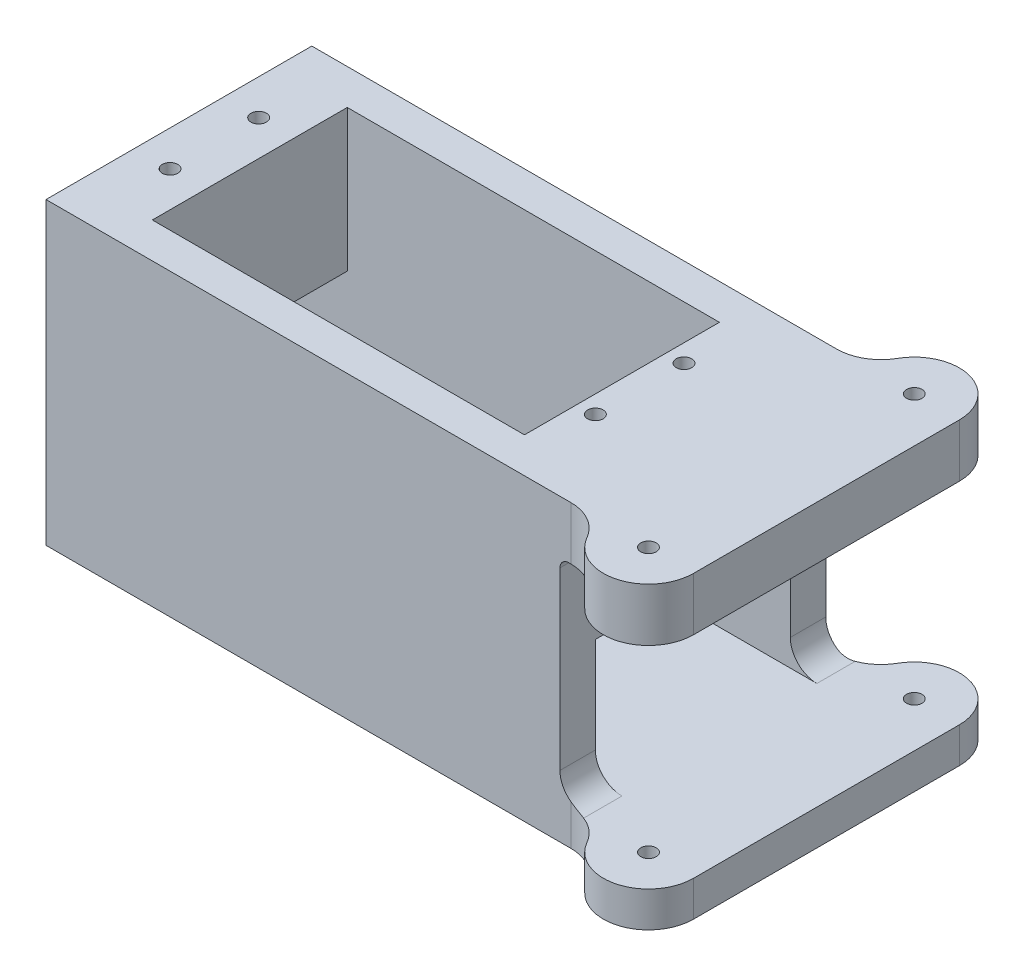
SolidWorks part; units mm, degrees
ref_plane "Front Plane" through (0, 0, 0) normal (0, 0, 1) x (1, 0, 0)
ref_plane "Top Plane" through (0, 0, 0) normal (0, 1, 0) x (1, 0, 0)
ref_plane "Right Plane" through (0, 0, 0) normal (1, 0, 0) x (0, 0, -1)
sketch "Sketch2" plane through (0, 0, 0) normal (0, 1, 0) x (1, 0, 0)
  line L0 (25, 15) -> (-25, 15)
  line L1 (21, 11) -> (-21, 11)
  line L2 (21, 11) -> (21, -11)
  line L3 (21, -11) -> (-21, -11)
  line L4 (-21, 11) -> (-21, -11)
  line L5 (21, 11) -> (-21, -11) construction
  line L6 (21, -11) -> (-21, 11) construction
  line L7 (-25, 15) -> (-25, -15)
  line L8 (25, -15) -> (-25, -15)
  line L9 (25, 15) -> (25, -15)
  point P0 (0, 0)
  dimension "D1" = 42
  dimension "D2" = 22
  dimension "D3" = 4
extrude "Boss-Extrude1" add sketch "Sketch2" along normal blind 28.8
sketch "Sketch3" plane through (0, 0, 0) normal (0, -1, 0) x (1, 0, 0)
  line L1 (25, 15) -> (-25, 15)
  line L2 (25, 15) -> (25, -15)
  line L3 (25, -15) -> (-25, -15)
  line L4 (-25, 15) -> (-25, -15)
  line L5 (25, 15) -> (-25, -15) construction
  line L6 (25, -15) -> (-25, 15) construction
  point P0 (0, 0)
extrude "Boss-Extrude2" add sketch "Sketch3" along normal blind 4
sketch "Sketch4" plane through (25, 0, 0) normal (1, 0, 0) x (0, 0, -1)
  line L0 (15, -4) -> (-15, -4) construction
  line L1 (-11, -4) -> (11, -4)
  line L2 (-11, -4) -> (-11, 13.8)
  line L3 (-11, 13.8) -> (11, 13.8)
  line L4 (11, -4) -> (11, 13.8)
  line L5 (-15, 28.8) -> (-15, -4) construction
  line L6 (15, 28.8) -> (15, -4) construction
  line L7 (-15, 28.8) -> (15, 28.8) construction
  dimension "D1" = 4
  dimension "D2" = 4
  dimension "D3" = 15
extrude "Cut-Extrude1" cut sketch "Sketch4" against normal blind 4
sketch "Sketch5" plane through (-25, 0, 0) normal (-1, 0, 0) x (0, 0, 1)
  line L4 (-15, 28.8) -> (-15, -4)
  line L5 (-15, -4) -> (15, -4)
  line L6 (15, -4) -> (15, 28.8)
  line L7 (15, 28.8) -> (-15, 28.8)
  line L8 (-15, 28.8) -> (-15, -4)
  line L9 (-15, -4) -> (15, -4)
  line L10 (15, -4) -> (15, 28.8)
  line L11 (15, 28.8) -> (-15, 28.8)
  dimension "D1" = 0
extrude "Boss-Extrude3" add sketch "Sketch5" along normal blind 4
sketch "Sketch6" plane through (25, 0, 0) normal (1, 0, 0) x (0, 0, -1)
  line L8 (-15, -4) -> (-11, -4)
  line L9 (-11, -4) -> (-11, 13.8)
  line L10 (-11, 13.8) -> (11, 13.8)
  line L11 (11, 13.8) -> (11, -4)
  line L12 (11, -4) -> (15, -4)
  line L13 (15, -4) -> (15, 28.8)
  line L14 (15, 28.8) -> (-15, 28.8)
  line L15 (-15, 28.8) -> (-15, -4)
  line L16 (-15, -4) -> (-11, -4)
  line L17 (-11, -4) -> (-11, 13.8)
  line L18 (-11, 13.8) -> (11, 13.8)
  line L19 (11, 13.8) -> (11, -4)
  line L20 (11, -4) -> (15, -4)
  line L21 (15, -4) -> (15, 28.8)
  line L22 (15, 28.8) -> (-15, 28.8)
  line L23 (-15, 28.8) -> (-15, -4)
  dimension "D1" = 0
extrude "Boss-Extrude4" add sketch "Sketch6" along normal blind 4
sketch "Sketch7" plane through (0, 28.8, 0) normal (0, 1, 0) x (1, 0, 0)
  circle A0 centre (23, -5) radius 0.875
  circle A1 centre (23, 5) radius 0.875
  circle A2 centre (-25, 5) radius 0.875
  circle A3 centre (-25, -5) radius 0.875
  dimension "D1" = 1.75
extrude "Cut-Extrude2" cut sketch "Sketch7" against normal blind 10
sketch "Sketch8" plane through (0, -4, 0) normal (0, -1, 0) x (1, 0, 0)
  line L0 (-29, -15) -> (29, -15) construction
  line L1 (38.9912, 15) -> (38.9912, -15) construction
  line L2 (20.903, -15) -> (30.2293, -15)
  line L3 (20.903, -15) -> (20.903, 15)
  line L4 (20.903, 15) -> (30.2293, 15)
  line L7 (44.0794, 15) -> (44.0794, -15)
  arc A2 (44.0794, 15) -> (34.5719, 17.5219) centre (38.9912, 15) ccw
  arc A3 (34.5719, -17.5219) -> (44.0794, -15) centre (38.9912, -15) ccw
  arc A4 (30.2293, 15) -> (34.5719, 17.5219) centre (30.2293, 20) ccw
  arc A5 (30.2293, -15) -> (34.5719, -17.5219) centre (30.2293, -20) cw
  circle A6 centre (38.9912, 15) radius 0.875
  circle A7 centre (38.9912, -15) radius 0.875
  point P8 (39.0381, 0)
  point P17 (33.903, 15)
  point P20 (33.903, -15)
  dimension "D3" = 5.0882
  dimension "D4" = 5.0882
  dimension "D6" = 5
  dimension "D7" = 1.75
  dimension "D1" = 13
  dimension "D2" = 30
  dimension "D5" = 30
extrude "Boss-Extrude5" add sketch "Sketch8" against normal up to surface (4 mm away) up to face at (0, 0, 0)
fillet "Fillet1" radius 3 2 edges at (29, 0, -13) (29, 0, 13)
ref_plane "Plane1" through (0, 12.4, 0) normal (0, 1, 0) x (1, 0, 0)
sketch "Sketch9" plane through (0, 28.8, 0) normal (0, 1, 0) x (1, 0, 0)
  line L0 (29, 15) -> (-29, 15) construction
  line L1 (30.2293, 15) -> (26.3329, 15)
  line L2 (26.3329, 15) -> (26.3329, -15)
  line L3 (-29, -15) -> (29, -15) construction
  line L4 (26.3329, -15) -> (30.2293, -15)
  line L6 (32, 15.3241) -> (32, 11)
  line L7 (32, 11) -> (-21, 11)
  line L8 (-21, 11) -> (-21, -11)
  line L9 (-21, -11) -> (32, -11)
  line L10 (32, -11) -> (32, -15.3241)
  line L11 (44.0794, -15) -> (44.0794, 15)
  line L17 (44.0794, -15) -> (44.0794, 15)
  arc A0 (32, 15.3241) -> (30.2293, 15) centre (30.2293, 20) cw
  arc A2 (30.2293, -15) -> (32, -15.3241) centre (30.2293, -20) cw
  circle A3 centre (38.9912, -15) radius 0.875
  arc A4 (32, 15.3241) -> (34.5719, 17.5219) centre (30.2293, 20) ccw
  arc A5 (34.5719, -17.5219) -> (32, -15.3241) centre (30.2293, -20) ccw
  arc A6 (34.5719, -17.5219) -> (44.0794, -15) centre (38.9912, -15) ccw
  arc A7 (44.0794, 15) -> (34.5719, 17.5219) centre (38.9912, 15) ccw
  arc A8 (32, 15.3241) -> (34.5719, 17.5219) centre (30.2293, 20) ccw
  arc A9 (34.5719, -17.5219) -> (32, -15.3241) centre (30.2293, -20) ccw
  arc A10 (34.5719, -17.5219) -> (44.0794, -15) centre (38.9912, -15) ccw
  arc A11 (44.0794, 15) -> (34.5719, 17.5219) centre (38.9912, 15) ccw
  circle A12 centre (38.9912, 15) radius 0.875
  dimension "D2" = 1.75
  dimension "D3" = 1.75
  dimension "D1" = 0
extrude "Boss-Extrude6" add sketch "Sketch9" against normal blind 5
fillet "Fillet2" radius 1 1 edges at (29, 23.8, 0)
sketch "Sketch11" plane through (0, 28.8, 0) normal (0, 1, 0) x (1, 0, 0)
  line L1 (21, 11) -> (-21, 11)
  line L2 (21, 11) -> (21, -11)
  line L3 (21, -11) -> (-21, -11)
  line L4 (-29, -15) -> (30.2293, -15)
  line L5 (44.0794, -15) -> (44.0794, 15)
  line L6 (30.2293, 15) -> (-29, 15)
  line L7 (-29, 15) -> (-29, -15)
  line L8 (-29, -15) -> (30.2293, -15)
  line L9 (44.0794, -15) -> (44.0794, 15)
  line L10 (30.2293, 15) -> (-29, 15)
  line L11 (-29, 15) -> (-29, -15)
  line L12 (-21, 11) -> (-21, -11)
  line L13 (21, 11) -> (-21, -11) construction
  line L14 (21, -11) -> (-21, 11) construction
  circle A0 centre (-25, 5) radius 0.875
  circle A1 centre (-25, -5) radius 0.875
  circle A2 centre (23, 5) radius 0.875
  circle A3 centre (23, -5) radius 0.875
  arc A4 (34.5719, -17.5219) -> (30.2293, -15) centre (30.2293, -20) ccw
  arc A5 (34.5719, -17.5219) -> (44.0794, -15) centre (38.9912, -15) ccw
  arc A6 (44.0794, 15) -> (34.5719, 17.5219) centre (38.9912, 15) ccw
  arc A7 (30.2293, 15) -> (34.5719, 17.5219) centre (30.2293, 20) ccw
  arc A8 (34.5719, -17.5219) -> (30.2293, -15) centre (30.2293, -20) ccw
  arc A9 (34.5719, -17.5219) -> (44.0794, -15) centre (38.9912, -15) ccw
  arc A10 (44.0794, 15) -> (34.5719, 17.5219) centre (38.9912, 15) ccw
  arc A11 (30.2293, 15) -> (34.5719, 17.5219) centre (30.2293, 20) ccw
  circle A12 centre (38.9912, -15) radius 0.875
  circle A13 centre (38.9912, 15) radius 0.875
  point P2 (0, 0)
  dimension "D1" = 0
extrude "Boss-Extrude7" add sketch "Sketch11" along normal blind 1
sketch "Sketch14" plane through (0, -4, 0) normal (0, -1, 0) x (1, 0, 0)
  line L0 (30.2293, 15) -> (-29, 15) construction
  line L1 (-29, -15) -> (-29, 15) construction
  circle A0 centre (10.09, 0) radius 5
  dimension "D3" = 10
  dimension "D1" = 15
  dimension "D2" = 39.09
extrude "Cut-Extrude3" cut sketch "Sketch14" against normal blind 37
sketch "Sketch15" plane through (0, 0, 0) normal (0, 1, 0) x (1, 0, 0)
  line L1 (-19, 7.5) -> (19, 7.5)
  line L2 (-19, 7.5) -> (-19, -7.5)
  line L3 (-19, -7.5) -> (19, -7.5)
  line L4 (19, 7.5) -> (19, -7.5)
  line L5 (-19, 7.5) -> (19, -7.5) construction
  line L6 (-19, -7.5) -> (19, 7.5) construction
  point P0 (0, 0)
  dimension "D1" = 38
  dimension "D2" = 15
ref_plane "Plane2" through (0, 0, 0) normal (-1, 0, 0) x (0, 0, 1)
sketch "Sketch17" plane through (0, 0, 0) normal (0, 1, 0) x (1, 0, 0)
  line L0 (0, 9.8615) -> (0, -10.9295) construction
  line L1 (0, 12.1) -> (0, -12.1) construction
  circle A0 centre (10.09, 0) radius 5 construction
  circle A2 centre (-10.09, 0) radius 7.5
  dimension "D1" = 15
extrude "Cut-Extrude4" cut sketch "Sketch17" against normal through all
sketch "Sketch18" plane through (0, -4, 0) normal (0, -1, 0) x (1, 0, 0)
  circle A0 centre (10.09, 0) radius 5 construction
  circle A1 centre (10.09, 0) radius 5
extrude "Boss-Extrude9" add sketch "Sketch18" against normal up to surface (4 mm away) up to face at (-10.09, 0, -7.5)
sketch "Sketch19" plane through (-21, 0, 0) normal (1, 0, 0) x (0, 0, -1)
  line L0 (-11, 13.8) -> (11, 13.8) construction
  line L1 (-11, 13.8) -> (11, 13.8)
  line L2 (-11, 3) -> (-11, 13.8) construction
  line L3 (-11, 3) -> (-11, 13.8)
  line L4 (-11, 3) -> (-11, 0)
  line L5 (15, 0) -> (-15, 0) construction
  line L6 (-11, 0) -> (11, 0)
  line L7 (11, 0) -> (11, 13.8)
extrude "Cut-Extrude5" cut sketch "Sketch19" against normal through all
